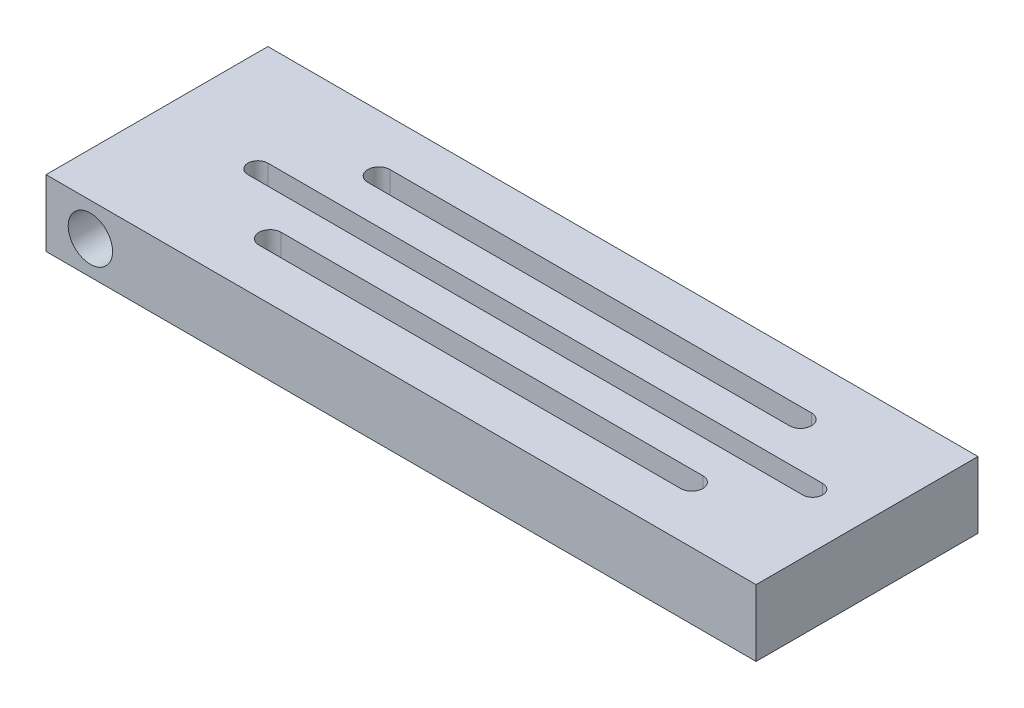
SolidWorks part; units mm, degrees
ref_plane "Front" through (0, 0, 0) normal (0, 0, 1) x (1, 0, 0)
ref_plane "Top" through (0, 0, 0) normal (0, 1, 0) x (1, 0, 0)
ref_plane "Right" through (0, 0, 0) normal (1, 0, 0) x (0, 0, -1)
sketch "Sketch1" plane through (0, 0, 0) normal (0, 1, 0) x (1, 0, 0)
  line L1 (-101.6, -31.75) -> (101.6, -31.75)
  line L2 (-101.6, -31.75) -> (-101.6, 31.75)
  line L3 (-101.6, 31.75) -> (101.6, 31.75)
  line L4 (101.6, -31.75) -> (101.6, 31.75)
  line L5 (-101.6, -31.75) -> (101.6, 31.75) construction
  line L6 (-101.6, 31.75) -> (101.6, -31.75) construction
  point P0 (0, 0)
  dimension "D1" = 203.2
  dimension "D2" = 63.5
extrude "Boss-Extrude1" add sketch "Sketch1" along normal mid plane 19.05 contours L3 L4 L1 L2
sketch "Sketch2" plane through (0, 9.525, 0) normal (0, 1, 0) x (1, 0, 0)
  line L0 (-72.7075, 0) -> (86.0425, 0) construction
  line L1 (-50, 0) -> (50, 0) construction
  line L2 (-72.7075, 2.8575) -> (86.0425, 2.8575)
  line L3 (-72.7075, -2.8575) -> (86.0425, -2.8575)
  line L4 (-53.6575, 15.5575) -> (66.9925, 15.5575) construction
  line L5 (-53.6575, 18.7325) -> (66.9925, 18.7325)
  line L6 (-53.6575, 12.3825) -> (66.9925, 12.3825)
  line L7 (-53.6575, -15.5575) -> (66.9925, -15.5575) construction
  line L8 (-53.6575, -12.3825) -> (66.9925, -12.3825)
  line L9 (-53.6575, -18.7325) -> (66.9925, -18.7325)
  line L10 (101.6, -31.75) -> (101.6, 31.75) construction
  arc A0 (-72.7075, 2.8575) -> (-72.7075, -2.8575) centre (-72.7075, 0) ccw
  arc A1 (86.0425, -2.8575) -> (86.0425, 2.8575) centre (86.0425, 0) ccw
  arc A2 (-53.6575, 18.7325) -> (-53.6575, 12.3825) centre (-53.6575, 15.5575) ccw
  arc A3 (66.9925, 12.3825) -> (66.9925, 18.7325) centre (66.9925, 15.5575) ccw
  arc A4 (-53.6575, -12.3825) -> (-53.6575, -18.7325) centre (-53.6575, -15.5575) ccw
  arc A5 (66.9925, -18.7325) -> (66.9925, -12.3825) centre (66.9925, -15.5575) ccw
  point P5 (6.6675, 0)
  point P12 (6.6675, 15.5575)
  point P17 (6.6675, -15.5575)
  point P27 (88.9, 0)
  point P28 (70.1675, 15.5575)
  dimension "D1" = 6.35
  dimension "D2" = 5.715
  dimension "D3" = 158.75
  dimension "D4" = 12.7
  dimension "D5" = 120.65
  dimension "D6" = 9.525
  dimension "D7" = 9.525
extrude "Cut-Extrude1" cut sketch "Sketch2" against normal through all
sketch "Sketch3" plane through (0, 0, -31.75) normal (0, 0, -1) x (-1, 0, 0)
  line L0 (50, 0) -> (-50, 0) construction
  line L1 (101.6, 9.525) -> (101.6, -9.525) construction
  circle A0 centre (88.9, 0) radius 6.35
  dimension "D1" = 12.7
  dimension "D2" = 12.7
extrude "Cut-Extrude2" cut sketch "Sketch3" against normal up to next
chamfer "Chamfer1" [suppressed] distance 1.27 angle 45
chamfer "Chamfer2" [suppressed] distance 1.27 angle 45
